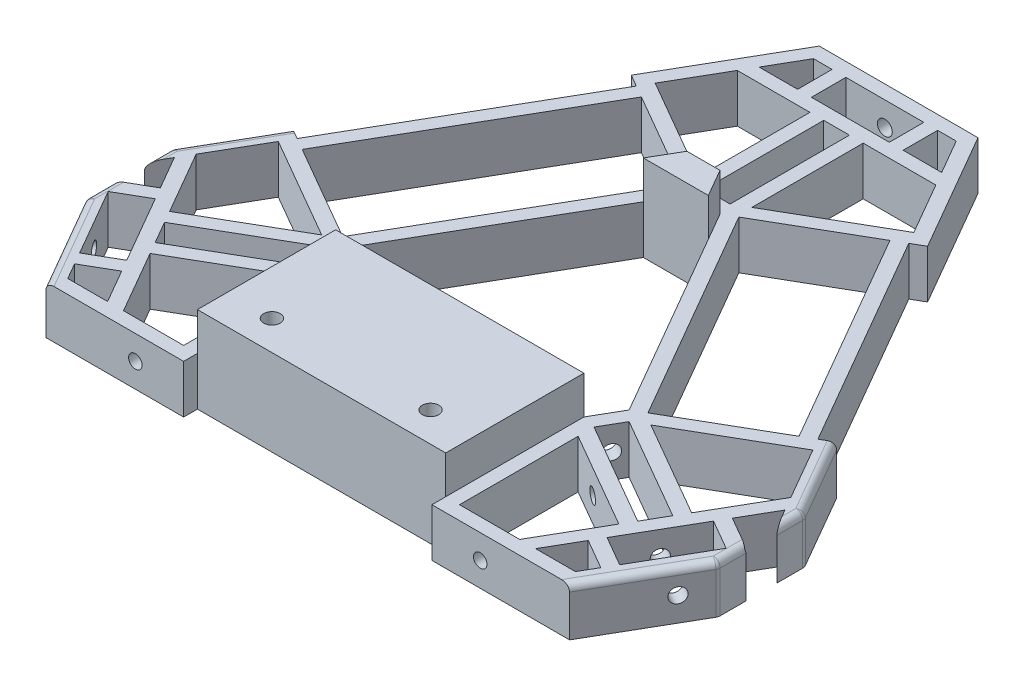
SolidWorks part; units mm, degrees
material "ABS"
ref_plane "正面" through (0, 0, 0) normal (0, 0, 1) x (1, 0, 0)
ref_plane "平面" through (0, 0, 0) normal (0, 1, 0) x (1, 0, 0)
ref_plane "右側面" through (0, 0, 0) normal (1, 0, 0) x (0, 0, -1)
sketch "ｽｹｯﾁ1" plane through (0, 0, 0) normal (0, 1, 0) x (1, 0, 0)
  line L0 (-10.35, 48.4686) -> (10.35, 48.4686)
  line L1 (10.35, 48.4686) -> (18.75, 33.9193)
  line L2 (18.75, 33.9193) -> (17.0179, 32.9193)
  line L21 (17.0179, 32.9193) -> (37.0179, -1.7217)
  line L22 (37.0179, -1.7217) -> (38.75, -0.7217)
  line L23 (38.75, -0.7217) -> (47.15, -15.2709)
  line L25 (36.8, -33.1976) -> (20, -33.1976)
  line L26 (20, -33.1976) -> (20, -31.1976)
  line L27 (20, -31.1976) -> (-20, -31.1976)
  line L28 (-20, -31.1976) -> (-20, -33.1976)
  line L31 (-38.75, -0.7217) -> (-37.0179, -1.7217)
  line L32 (-37.0179, -1.7217) -> (-17.0179, 32.9193)
  line L33 (-17.0179, 32.9193) -> (-18.75, 33.9193)
  line L35 (-38.75, -0.7217) -> (-47.15, -15.2709)
  line L36 (-47.15, -15.2709) -> (-36.8, -33.1976)
  line L37 (-36.8, -33.1976) -> (-20, -33.1976)
  line L38 (-18.75, 33.9193) -> (-10.35, 48.4686)
  line L39 (36.8, -33.1976) -> (47.15, -15.2709)
  line L40 (-41.975, -24.2343) -> (27.0179, 15.5988) construction
  line L41 (0, 48.4686) -> (0, -31.1976) construction
  line L42 (41.975, -24.2343) -> (-27.0179, 15.5988) construction
  line L45 (-18, -33.1976) -> (18, -33.1976)
  line L57 (18, -33.1976) -> (18, -35.1976)
  line L58 (18, -35.1976) -> (37.9547, -35.1976)
  line L60 (37.9547, -35.1976) -> (49.4594, -15.2709)
  line L61 (49.4594, -15.2709) -> (39.4821, 2.0104)
  line L62 (39.4821, 2.0104) -> (37.75, 1.0104)
  line L63 (37.75, 1.0104) -> (19.75, 32.1873)
  line L64 (19.75, 32.1873) -> (21.4821, 33.1873)
  line L65 (21.4821, 33.1873) -> (11.5047, 50.4686)
  line L66 (11.5047, 50.4686) -> (-11.5047, 50.4686)
  line L67 (-11.5047, 50.4686) -> (-21.4821, 33.1873)
  line L68 (-21.4821, 33.1873) -> (-19.75, 32.1873)
  line L69 (-19.75, 32.1873) -> (-37.75, 1.0104)
  line L70 (-37.75, 1.0104) -> (-39.4821, 2.0104)
  line L71 (-39.4821, 2.0104) -> (-49.4594, -15.2709)
  line L72 (-49.4594, -15.2709) -> (-37.9547, -35.1976)
  line L73 (-37.9547, -35.1976) -> (-18, -35.1976)
  line L74 (-18, -35.1976) -> (-18, -33.1976)
  point P24 (0, 0)
  point P36 (17.884, 33.4193)
  dimension "D1" = 2
  dimension "D2" = 2
  dimension "D3" = 2
  dimension "D4" = 2
  dimension "D5" = 16.8
  dimension "D6" = 20.7
  dimension "D7" = 40
  dimension "D8" = 2
  dimension "D9" = 2
  dimension "D10" = 2
  dimension "D11" = 2
  dimension "D12" = 2
  dimension "D13" = 2
  dimension "D14" = 2
  dimension "D15" = 2
  dimension "D16" = 2
  dimension "D17" = 2
  dimension "D18" = 2
  dimension "D19" = 2
  dimension "D20" = 2
  dimension "D21" = 2
extrude "ﾎﾞｽ - 押し出し1" add sketch "ｽｹｯﾁ1" along normal blind 7
sketch "ｽｹｯﾁ3" plane through (0, 0, 0) normal (0, -1, 0) x (1, 0, 0)
  line L2 (-20, 13.6976) -> (-20, 31.1976)
  line L3 (-20, 31.1976) -> (-18, 31.1976)
  line L4 (-20, 31.1976) -> (20, 31.1976) construction
  line L5 (-18, 31.1976) -> (-18, 15.1617)
  line L8 (-17.0179, -32.9193) -> (-37.0179, 1.7217) construction
  line L9 (-37.0179, 1.7217) -> (-36.0179, -0.0104)
  line L10 (-37.0179, 1.7217) -> (-21.8625, 10.4717)
  line L11 (-21.8625, 10.4717) -> (-20, 13.6976)
  line L12 (-36.0179, -0.0104) -> (-22.1305, 8.0076)
  line L13 (-20.3984, 9.0076) -> (-18, 13.1617)
  line L14 (-47.15, 15.2709) -> (-36.8, 33.1976) construction
  line L15 (20, 31.1976) -> (20, 13.6976)
  line L16 (20, 13.6976) -> (21.8625, 10.4717)
  line L17 (21.8625, 10.4717) -> (37.0179, 1.7217)
  line L18 (37.0179, 1.7217) -> (36.0179, -0.0104)
  line L19 (37.0179, 1.7217) -> (17.0179, -32.9193) construction
  line L20 (36.0179, -0.0104) -> (22.1305, 8.0076)
  line L21 (20.3984, 9.0076) -> (18, 13.1617)
  line L22 (18, 15.1617) -> (18, 31.1976)
  line L23 (18, 31.1976) -> (20, 31.1976)
  line L24 (36.8, 33.1976) -> (47.15, 15.2709) construction
  line L25 (17.0179, -32.9193) -> (1.8625, -24.1693)
  line L26 (1.8625, -24.1693) -> (-1.8625, -24.1693)
  line L27 (-1.8625, -24.1693) -> (-17.0179, -32.9193)
  line L28 (-17.0179, -32.9193) -> (-18.0179, -31.1873)
  line L29 (-18.0179, -31.1873) -> (-4.1305, -23.1693)
  line L30 (-2.3984, -22.1693) -> (2.3984, -22.1693)
  line L31 (4.1305, -23.1693) -> (18.0179, -31.1873)
  line L32 (10.35, -48.4686) -> (-10.35, -48.4686) construction
  line L33 (18.0179, -31.1873) -> (17.0179, -32.9193)
  line L34 (18, 13.1617) -> (-18, 13.1617)
  line L35 (-20.3984, 9.0076) -> (-2.3984, -22.1693)
  line L36 (20.3984, 9.0076) -> (2.3984, -22.1693)
  line L37 (18, 15.1617) -> (-18, 15.1617)
  line L38 (22.1305, 8.0076) -> (4.1305, -23.1693)
  line L39 (-22.1305, 8.0076) -> (-4.1305, -23.1693)
  dimension "D1" = 2
  dimension "D2" = 2
  dimension "D3" = 2
  dimension "D4" = 17.5
  dimension "D5" = 17.5
  dimension "D6" = 2
  dimension "D7" = 2
  dimension "D8" = 2
  dimension "D9" = 17.5
  dimension "D10" = 2
  dimension "D11" = 2
  dimension "D12" = 2
  dimension "D13" = 2
  dimension "D14" = 2
  dimension "D15" = 2
  dimension "D16" = 2
  dimension "D17" = 2
  dimension "D18" = 2
extrude "ﾎﾞｽ - 押し出し2" add sketch "ｽｹｯﾁ3" against normal up to surface (7 mm away) up to face at (0, 7, 0)
sketch "ｽｹｯﾁ4" plane through (0, 0, 0) normal (0, -1, 0) x (1, 0, 0)
  line L0 (31.0265, 33.1976) -> (33.8199, 28.3594)
  line L1 (20, 33.1976) -> (36.8, 33.1976) construction
  line L2 (47.15, 15.2709) -> (38.75, 0.7217) construction
  line L3 (44.2632, 10.2709) -> (43.1085, 8.2709)
  line L4 (43.1085, 8.2709) -> (37.8441, 17.3893)
  line L5 (28.7171, 33.1976) -> (31.0265, 33.1976)
  line L6 (-31.0265, 33.1976) -> (-28.7171, 33.1976)
  line L7 (-36.8, 33.1976) -> (-20, 33.1976) construction
  line L8 (-28.7171, 33.1976) -> (-33.9816, 24.0793)
  line L9 (-38.75, 0.7217) -> (-47.15, 15.2709) construction
  line L10 (-43.1085, 8.2709) -> (-44.2632, 10.2709)
  line L11 (-31.0265, 33.1976) -> (-33.8199, 28.3594)
  line L12 (-14.3915, -41.4686) -> (-3.8625, -41.4686)
  line L13 (-10.35, -48.4686) -> (-18.75, -33.9193) construction
  line L14 (14.3915, -41.4686) -> (13.2368, -43.4686)
  line L15 (18.75, -33.9193) -> (10.35, -48.4686) construction
  line L16 (13.2368, -43.4686) -> (7.65, -43.4686)
  line L17 (-13.2368, -43.4686) -> (-14.3915, -41.4686)
  line L18 (36.8, 33.1976) -> (47.15, 15.2709) construction
  line L19 (10.35, -48.4686) -> (-10.35, -48.4686) construction
  line L20 (-47.15, 15.2709) -> (-36.8, 33.1976) construction
  line L21 (-20, 13.6976) -> (-34.9816, 22.3473)
  line L23 (-33.9816, 24.0793) -> (-20, 16.007)
  line L24 (-20, 33.1976) -> (-20, 13.6976) construction
  line L25 (-20, 16.007) -> (-20, 13.6976)
  line L26 (-21.8625, 10.4717) -> (-36.8441, 19.1213)
  line L28 (-37.8441, 17.3893) -> (-23.8625, 9.317)
  line L29 (-21.8625, 10.4717) -> (-38.75, 0.7217) construction
  line L30 (-23.8625, 9.317) -> (-21.8625, 10.4717)
  line L31 (20, 13.6976) -> (34.9816, 22.3473)
  line L33 (33.9816, 24.0793) -> (20, 16.007)
  line L34 (20, 13.6976) -> (20, 33.1976) construction
  line L35 (20, 16.007) -> (20, 13.6976)
  line L36 (21.8625, 10.4717) -> (36.8441, 19.1213)
  line L38 (37.8441, 17.3893) -> (23.8625, 9.317)
  line L39 (38.75, 0.7217) -> (21.8625, 10.4717) construction
  line L40 (23.8625, 9.317) -> (21.8625, 10.4717)
  line L41 (1.8625, -24.1693) -> (1.8625, -41.4686)
  line L43 (3.8625, -41.4686) -> (3.8625, -25.324)
  line L44 (1.8625, -24.1693) -> (18.75, -33.9193) construction
  line L45 (3.8625, -25.324) -> (1.8625, -24.1693)
  line L46 (-1.8625, -24.1693) -> (-1.8625, -41.4686)
  line L48 (-3.8625, -41.4686) -> (-3.8625, -25.324)
  line L49 (-18.75, -33.9193) -> (-1.8625, -24.1693) construction
  line L50 (-3.8625, -25.324) -> (-1.8625, -24.1693)
  line L51 (3.8625, -41.4686) -> (14.3915, -41.4686)
  line L52 (-1.8625, -41.4686) -> (1.8625, -41.4686)
  line L53 (33.9816, 24.0793) -> (28.7171, 33.1976)
  line L54 (36.8441, 19.1213) -> (34.9816, 22.3473)
  line L55 (-34.9816, 22.3473) -> (-36.8441, 19.1213)
  line L56 (-37.8441, 17.3893) -> (-43.1085, 8.2709)
  line L57 (33.8199, 28.3594) -> (38.15, 30.8594)
  line L58 (38.15, 30.8594) -> (39.15, 29.1273)
  line L59 (39.15, 29.1273) -> (34.8199, 26.6273)
  line L61 (40.4699, 16.8412) -> (44.8, 19.3412)
  line L62 (44.8, 19.3412) -> (45.8, 17.6092)
  line L63 (45.8, 17.6092) -> (41.4699, 15.1092)
  line L65 (-33.8199, 28.3594) -> (-38.15, 30.8594)
  line L66 (-38.15, 30.8594) -> (-39.15, 29.1273)
  line L67 (-39.15, 29.1273) -> (-34.8199, 26.6273)
  line L69 (-45.8, 17.6092) -> (-44.8, 19.3412)
  line L70 (-44.8, 19.3412) -> (-40.4699, 16.8412)
  line L72 (-41.4699, 15.1092) -> (-45.8, 17.6092)
  line L73 (5.65, -43.4686) -> (5.65, -48.4686)
  line L74 (5.65, -48.4686) -> (7.65, -48.4686)
  line L75 (7.65, -48.4686) -> (7.65, -43.4686)
  line L77 (-7.65, -43.4686) -> (-7.65, -48.4686)
  line L78 (-7.65, -48.4686) -> (-5.65, -48.4686)
  line L79 (-5.65, -48.4686) -> (-5.65, -43.4686)
  line L81 (41.4699, 15.1092) -> (44.2632, 10.2709)
  line L82 (34.8199, 26.6273) -> (40.4699, 16.8412)
  line L83 (-34.8199, 26.6273) -> (-40.4699, 16.8412)
  line L84 (-41.4699, 15.1092) -> (-44.2632, 10.2709)
  line L85 (5.65, -43.4686) -> (-5.65, -43.4686)
  line L86 (-7.65, -43.4686) -> (-13.2368, -43.4686)
  point P30 (9.127, -41.4686)
  point P73 (-30.8533, 13.3531)
  point P98 (41.975, 24.2343)
  point P99 (-41.975, 24.2343)
  point P101 (0, -48.4686)
  dimension "D1" = 5
  dimension "D2" = 2
  dimension "D3" = 5
  dimension "D4" = 2
  dimension "D5" = 5
  dimension "D6" = 2
  dimension "D7" = 2
  dimension "D8" = 2
  dimension "D9" = 2
  dimension "D10" = 2
  dimension "D11" = 2
  dimension "D12" = 2
  dimension "D13" = 5.65
  dimension "D14" = 11.3
  dimension "D15" = 2
  dimension "D16" = 2
  dimension "D17" = 5.65
  dimension "D18" = 11.3
  dimension "D19" = 2
  dimension "D20" = 2
  dimension "D21" = 5.65
  dimension "D22" = 11.3
  dimension "D23" = 2
  dimension "D24" = 2
extrude "ﾎﾞｽ - 押し出し3" add sketch "ｽｹｯﾁ4" against normal up to surface (7 mm away) up to face at (-30.7604, 7, 17.7595)
sketch "ｽｹｯﾁ5" plane through (43.7071, 0, 25.2343) normal (0.866, 0, 0.5) x (0.5, 0, -0.866)
  line L0 (-11.5047, 3.5) -> (11.5047, 3.5) construction
  line L1 (-11.5047, 7) -> (-11.5047, 0) construction
  line L2 (11.5047, 7) -> (11.5047, 0) construction
  circle A0 centre (0, 3.5) radius 1.075
  dimension "D1" = 2.15
extrude "ｶｯﾄ - 押し出し1" cut sketch "ｽｹｯﾁ5" against normal up to surface (28.2992 mm away) up to face at (19.1992, 3.5, 11.0847)
sketch "ｽｹｯﾁ6" plane through (0, 0, -50.4686) normal (0, 0, -1) x (-1, 0, 0)
  line L0 (-11.5047, 3.5) -> (11.5047, 3.5) construction
  line L1 (-11.5047, 7) -> (-11.5047, 0) construction
  line L2 (11.5047, 7) -> (11.5047, 0) construction
  circle A0 centre (0, 3.5) radius 1.075
  dimension "D1" = 2.15
extrude "ｶｯﾄ - 押し出し2" cut sketch "ｽｹｯﾁ6" against normal up to surface (28.2992 mm away) up to face at (0, 3.5, -22.1693)
sketch "ｽｹｯﾁ7" plane through (-43.7071, 0, 25.2343) normal (-0.866, 0, 0.5) x (0.5, 0, 0.866)
  line L0 (-11.5047, 3.5) -> (11.5047, 3.5) construction
  line L1 (-11.5047, 7) -> (-11.5047, 0) construction
  line L2 (11.5047, 7) -> (11.5047, 0) construction
  circle A0 centre (0, 3.5) radius 1.075
  dimension "D1" = 2.15
extrude "ｶｯﾄ - 押し出し3" cut sketch "ｽｹｯﾁ7" against normal up to surface (28.2992 mm away) up to face at (-19.1992, 3.5, 11.0847)
sketch "ｽｹｯﾁ8" plane through (0, 7, 0) normal (0, 1, 0) x (1, 0, 0)
  line L0 (18, -15.1617) -> (-18, -31.1976) construction
  line L2 (-18, -31.1976) -> (18, -31.1976)
  line L3 (-18, -31.1976) -> (-18, -15.1617)
  line L4 (-18, -15.1617) -> (18, -15.1617)
  line L5 (18, -31.1976) -> (18, -15.1617)
  line L6 (-18, -31.1976) -> (18, -15.1617) construction
  line L7 (-18, -15.1617) -> (18, -31.1976) construction
  point P4 (0, -23.1797)
extrude "ﾎﾞｽ - 押し出し4" add sketch "ｽｹｯﾁ8" against normal blind 7
sketch "ｽｹｯﾁ9" plane through (0, 7, 0) normal (0, 1, 0) x (1, 0, 0)
  line L0 (-18, -13.1617) -> (-18, -33.1976)
  line L1 (-18, -33.1976) -> (18, -33.1976)
  line L2 (18, -33.1976) -> (18, -13.1617)
  line L3 (18, -13.1617) -> (-18, -13.1617)
extrude "ﾎﾞｽ - 押し出し5" add sketch "ｽｹｯﾁ9" along normal blind 5.5
sketch "ｽｹｯﾁ10" plane through (0, 12.5, 0) normal (0, 1, 0) x (1, 0, 0)
  line L0 (-18, -28.8976) -> (18, -28.8976) construction
  line L1 (-18, -13.1617) -> (-18, -33.1976) construction
  line L2 (18, -33.1976) -> (18, -13.1617) construction
  line L3 (-18, -33.1976) -> (18, -33.1976) construction
  circle A0 centre (-11.5, -28.8976) radius 1.2
  circle A1 centre (11.5, -28.8976) radius 1.2
  point P12 (0, -28.8976)
  dimension "D2" = 2.4
  dimension "D3" = 2.4
  dimension "D4" = 23
  dimension "D5" = 11.5
  dimension "D1" = 4.3
extrude "ｶｯﾄ - 押し出し4" cut sketch "ｽｹｯﾁ10" against normal through all
fillet "ﾌｨﾚｯﾄ1" radius 8 2 edges at (49.4594, 3.5, 15.2709) (-49.4594, 3.5, 15.2709)
sketch "ｽｹｯﾁ12" plane through (0, 7, 0) normal (0, 1, 0) x (1, 0, 0)
  line L15 (0, -64.0294) -> (0, 75.5944) construction
  line L16 (-91.6508, -9.1976) -> (94.0489, -9.1976) construction
  line L17 (-37.9547, -35.1976) -> (-18, -35.1976) construction
  line L18 (-47.15, -19.2709) -> (-37.9547, -35.1976) construction
  line L19 (-54.15, 3.1273) -> (-45.85, 3.1273)
  line L20 (-54.15, 3.1273) -> (-54.15, -21.5226)
  line L21 (-54.15, -21.5226) -> (-45.85, -21.5226)
  line L22 (-45.85, 3.1273) -> (-45.85, -21.5226)
  line L23 (-54.15, 3.1273) -> (-45.85, -21.5226) construction
  line L24 (-54.15, -21.5226) -> (-45.85, 3.1273) construction
  line L25 (37.9547, -35.1976) -> (47.15, -19.2709) construction
  line L26 (54.15, 3.1273) -> (45.85, 3.1273)
  line L27 (54.15, 3.1273) -> (54.15, -21.5226)
  line L28 (54.15, -21.5226) -> (45.85, -21.5226)
  line L29 (45.85, 3.1273) -> (45.85, -21.5226)
  line L30 (54.15, 3.1273) -> (45.85, -21.5226) construction
  line L31 (54.15, -21.5226) -> (45.85, 3.1273) construction
  point P8 (-50, -9.1976)
  point P17 (50, -9.1976)
  dimension "D1" = 26
  dimension "D2" = 8.3
  dimension "D3" = 50
  dimension "D4" = 50
extrude "ｶｯﾄ - 押し出し6" cut sketch "ｽｹｯﾁ12" against normal through all
fillet "ﾌｨﾚｯﾄ2" radius 1 12 edges at (42.666, 7, 3.5044) (45.85, 3.5, 9.0192) (45.85, 7, 11.0192) (45.85, 7, 19.5226) (45.85, 3.5, 21.5226) (41.9024, 7, 28.3601) (-41.9024, 7, 28.3601) (-45.85, 7, 19.5226) (-45.85, 3.5, 21.5226) (-45.85, 3.5, 9.0192) (-42.666, 7, 3.5044) (-45.85, 7, 11.0192)
sketch "ｽｹｯﾁ13" plane through (0, 0, 0) normal (0, -1, 0) x (1, 0, 0)
  circle A0 centre (11.5, 28.8976) radius 2.5
  circle A1 centre (-11.5, 28.8976) radius 2.5
  dimension "D1" = 5
  dimension "D2" = 5
extrude "ｶｯﾄ - 押し出し7" cut sketch "ｽｹｯﾁ13" against normal blind 3
sketch "ｽｹｯﾁ15" plane through (0, 0, 0) normal (0, -1, 0) x (1, 0, 0)
  line L0 (2.3984, -22.1693) -> (4.7078, -18.1693)
  line L1 (2.3984, -22.1693) -> (20.3984, 9.0076) construction
  line L2 (4.7078, -18.1693) -> (-4.7078, -18.1693)
  line L3 (-20.3984, 9.0076) -> (-2.3984, -22.1693) construction
  line L4 (-4.7078, -18.1693) -> (-2.3984, -22.1693)
  line L5 (-2.3984, -22.1693) -> (2.3984, -22.1693)
  dimension "D1" = 4
extrude "ﾎﾞｽ - 押し出し6" add sketch "ｽｹｯﾁ15" against normal blind 12.5
sketch "ｽｹｯﾁ16" plane through (0, 0, 35.1976) normal (0, 0, 1) x (1, 0, 0)
  line L0 (-17.0116, 3.5) -> (38.9431, 3.5) construction
  line L3 (-18, 7) -> (-18, 0) construction
  line L4 (18, 7) -> (18, 0) construction
  line L5 (-37.9547, 0) -> (-18, 0) construction
  circle A0 centre (-25, 3.5) radius 0.975
  circle A1 centre (25, 3.5) radius 0.975
  dimension "D1" = 7
  dimension "D2" = 7
  dimension "D3" = 1.95
  dimension "D4" = 1.95
  dimension "D5" = 3.5
extrude "ｶｯﾄ - 押し出し8" cut sketch "ｽｹｯﾁ16" against normal blind 20
